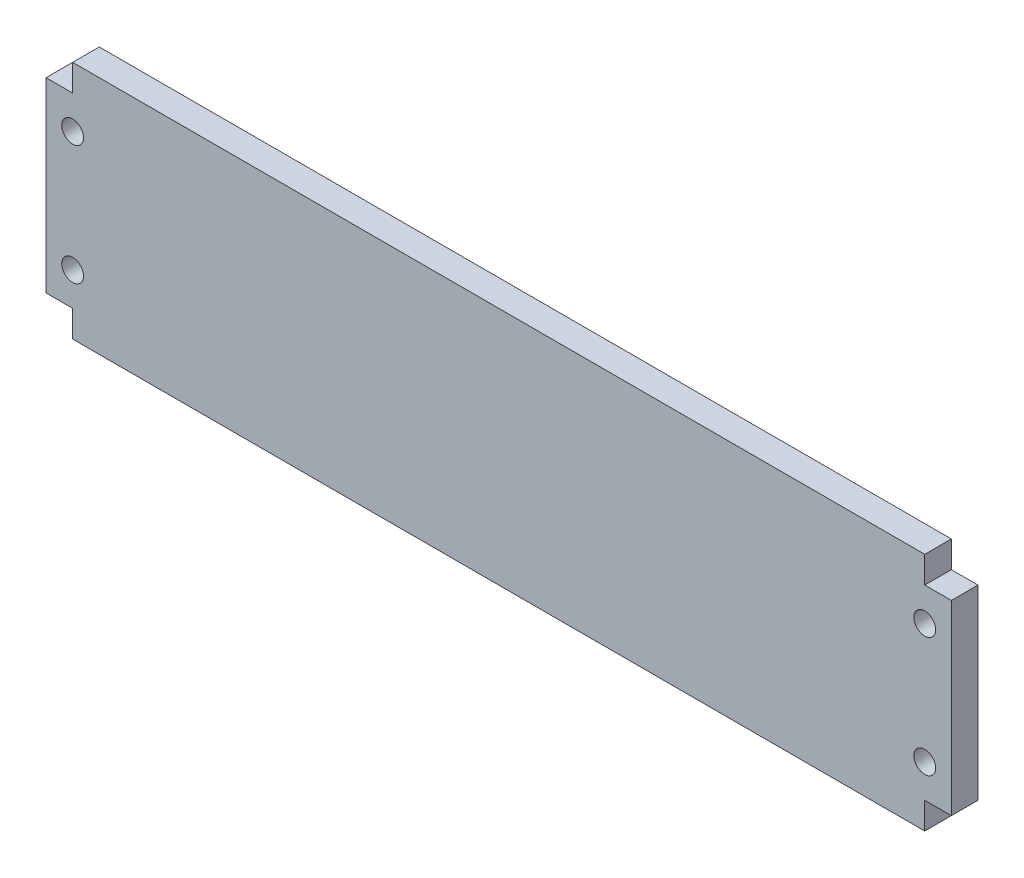
SolidWorks part; units mm, degrees
ref_plane "Alzado" through (0, 0, 0) normal (0, 0, 1) x (1, 0, 0)
ref_plane "Planta" through (0, 0, 0) normal (0, 1, 0) x (1, 0, 0)
ref_plane "Vista lateral" through (0, 0, 0) normal (1, 0, 0) x (0, 0, -1)
sketch "Croquis1" plane through (0, 0, 0) normal (0, 0, 1) x (1, 0, 0)
  line L0 (85, 22.5) -> (-85, 22.5)
  line L1 (-85, 22.5) -> (-85, -22.5)
  line L2 (0, 0) -> (-3.4544, 0) construction
  line L3 (0, 0) -> (0, 11.2967) construction
  line L4 (85, 22.5) -> (85, -22.5)
  line L5 (85, -22.5) -> (-85, -22.5)
  point P9 (0, 22.5)
  point P10 (85, 0)
  point P11 (-85, 0)
  dimension "D1" = 22.5
  dimension "D2" = 85
extrude "Saliente-Extruir1" add sketch "Croquis1" along normal blind 5
sketch "Croquis2" plane through (0, 0, 5) normal (0, 0, 1) x (1, 0, 0)
  line L4 (85, 22.5) -> (-85, 22.5) construction
  line L5 (-80, 22.5) -> (-85, 22.5)
  line L6 (0, 0) -> (0, 15.2772) construction
  line L11 (-85, 22.5) -> (-85, 17.5)
  line L12 (-85, 22.5) -> (-85, -22.5) construction
  line L13 (-80, 22.5) -> (-80, 17.5)
  line L14 (-80, 17.5) -> (-85, 17.5)
  line L15 (-80, -22.5) -> (-80, -17.5)
  line L17 (-80, -22.5) -> (-85, -22.5)
  line L18 (-85, -22.5) -> (-85, -17.5)
  line L19 (0, 0) -> (-13.0884, 0) construction
  line L20 (-80, -17.5) -> (-85, -17.5)
  line L21 (80, -22.5) -> (85, -22.5)
  line L22 (85, -22.5) -> (85, -17.5)
  line L23 (80, -17.5) -> (85, -17.5)
  line L24 (80, -22.5) -> (80, -17.5)
  line L25 (80, 22.5) -> (80, 17.5)
  line L26 (80, 22.5) -> (85, 22.5)
  line L27 (85, 22.5) -> (85, 17.5)
  line L28 (80, 17.5) -> (85, 17.5)
  dimension "D1" = 5
  dimension "D2" = 5
extrude "Cortar-Extruir1" cut sketch "Croquis2" against normal blind 10
sketch "Croquis4" plane through (0, 0, 0) normal (0, 0, -1) x (-1, 0, 0)
  line L0 (-72.7487, -12.731) -> (5.2743, -12.731) construction
  text T0 "Robot Rescue Batterys\r\n" font "Century Gothic" height in points 16
extrude "Saliente-Extruir4" add sketch "Croquis4" along normal blind 2
sketch "Croquis5" plane through (0, 0, 0) normal (0, 0, -1) x (-1, 0, 0)
  line L0 (-80, 22.5) -> (-80, 0) construction
  line L1 (-80, 0) -> (-85, 0) construction
  line L2 (-85, -17.5) -> (-85, 17.5) construction
  line L3 (0, 0) -> (0, 12.7085) construction
  circle A4 centre (-80, 11.25) radius 2.05
  circle A5 centre (-80, -11.25) radius 2.05
  circle A6 centre (80, -11.25) radius 2.05
  circle A7 centre (80, 11.25) radius 2.05
  dimension "D1" = 4.1
extrude "Cortar-Extruir2" cut sketch "Croquis5" against normal blind 10
